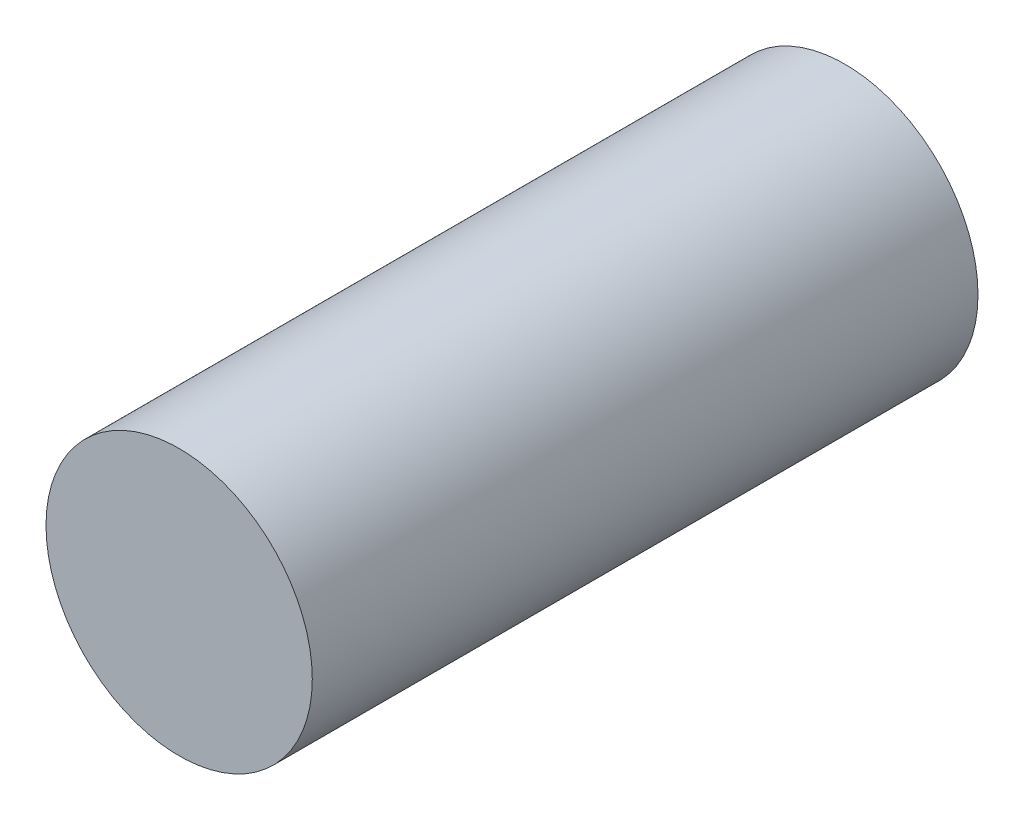
SolidWorks part; units mm, degrees
ref_plane "Front Plane" through (0, 0, 0) normal (0, 0, 1) x (1, 0, 0)
ref_plane "Top Plane" through (0, 0, 0) normal (0, 1, 0) x (1, 0, 0)
ref_plane "Right Plane" through (0, 0, 0) normal (1, 0, 0) x (0, 0, -1)
sketch "Sketch1" plane through (0, 0, 0) normal (0, 0, 1) x (1, 0, 0)
  circle A0 centre (0, 0) radius 3
extrude "Boss-Extrude1" add sketch "Sketch1" along normal blind 15
